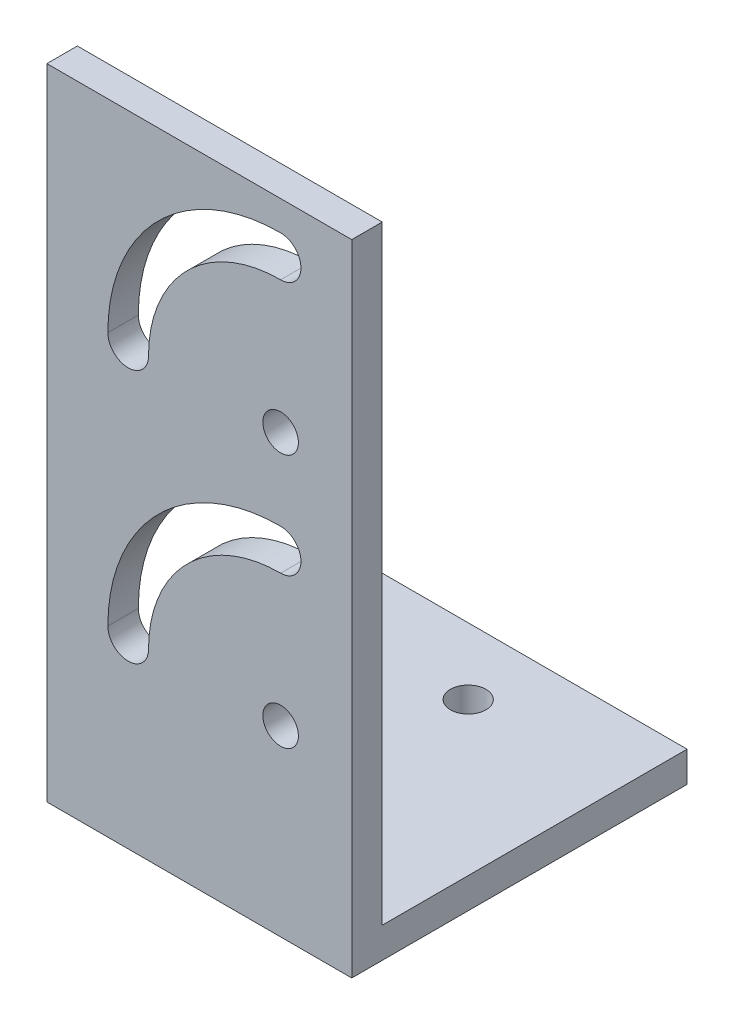
SolidWorks part; units mm, degrees
ref_plane "前视基准面" through (0, 0, 0) normal (0, 0, 1) x (1, 0, 0)
ref_plane "上视基准面" through (0, 0, 0) normal (0, 1, 0) x (1, 0, 0)
ref_plane "右视基准面" through (0, 0, 0) normal (1, 0, 0) x (0, 0, -1)
sketch "草图1" plane through (0, 0, 0) normal (0, 1, 0) x (1, 0, 0)
  line L1 (-15, -15) -> (15, -15)
  line L2 (-15, -15) -> (-15, 15)
  line L3 (-15, 15) -> (15, 15)
  line L4 (15, -15) -> (15, 15)
  line L5 (-15, -15) -> (15, 15) construction
  line L6 (-15, 15) -> (15, -15) construction
  point P1 (0, 0)
  dimension "D1" = 30
  dimension "D2" = 30
extrude "凸台-拉伸1" add sketch "草图1" along normal blind 3
sketch "草图2" plane through (0, 3, 0) normal (0, 1, 0) x (1, 0, 0)
  circle A0 centre (0, -6.5427) radius 1.75
  circle A1 centre (0, 8.4573) radius 1.75
  dimension "D1" = 15
extrude "切除-拉伸1" cut sketch "草图2" against normal blind 3
sketch "草图3" plane through (0, 0, 15) normal (0, 0, 1) x (1, 0, 0)
  line L1 (-15, 0) -> (15, 0)
  line L2 (-15, 0) -> (-15, 62.9242)
  line L3 (-15, 62.9242) -> (15, 62.9242)
  line L4 (15, 0) -> (15, 62.9242)
extrude "凸台-拉伸2" add sketch "草图3" along normal blind 3
sketch "草图4" plane through (0, 0, 18) normal (0, 0, 1) x (1, 0, 0)
  line L0 (15, 0) -> (15, 62.9242) construction
  circle A11 centre (8, 43) radius 1.75
  arc A12 (8, 60) -> (8, 56) centre (8, 58) cw
  arc A13 (-9, 43) -> (8, 60) centre (8, 43) cw
  arc A14 (-5, 43) -> (8, 56) centre (8, 43) cw
  arc A15 (-5, 43) -> (-9, 43) centre (-7, 43) cw
  circle A16 centre (8, 18) radius 1.75
  arc A17 (-5, 18) -> (-9, 18) centre (-7, 18) cw
  arc A18 (8, 35) -> (8, 31) centre (8, 33) cw
  arc A19 (-9, 18) -> (8, 35) centre (8, 18) cw
  arc A20 (-5, 18) -> (8, 31) centre (8, 18) cw
  point P0 (0, 0)
  dimension "D1" = 7
  dimension "D2" = 7
extrude "切除-拉伸2" cut sketch "草图4" against normal blind 3
